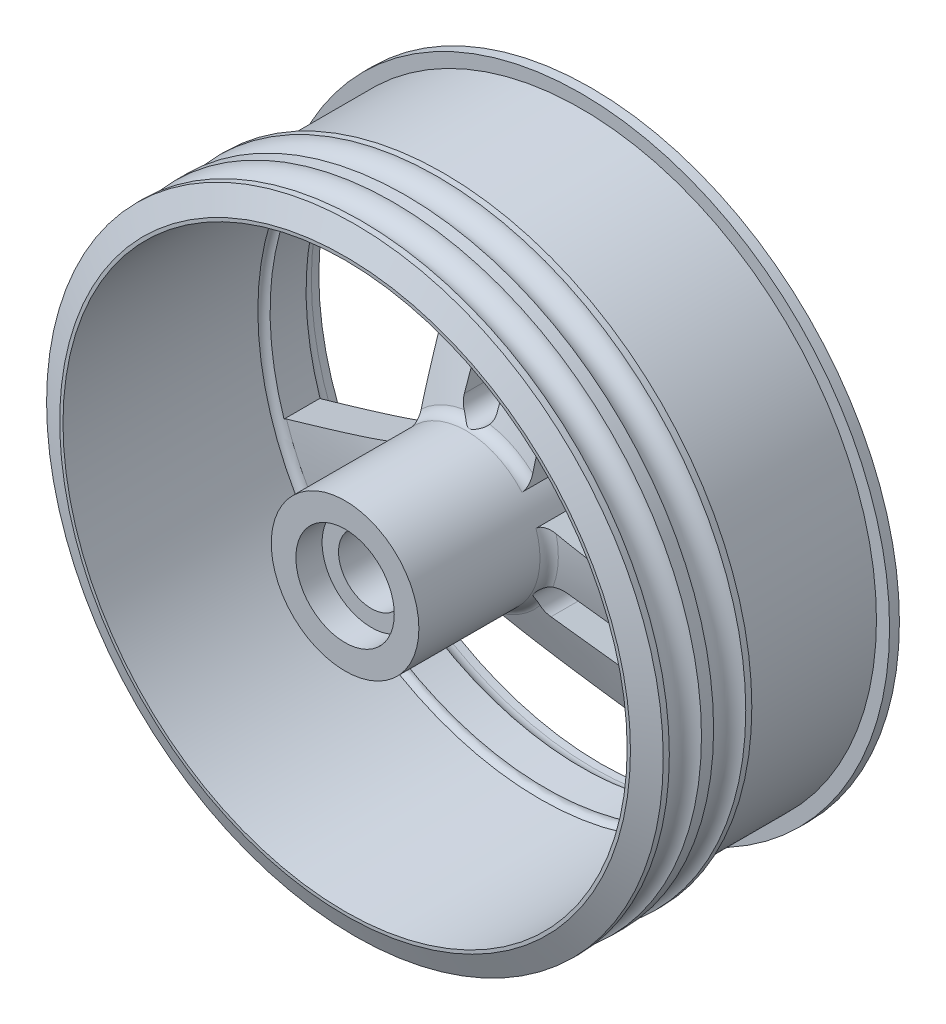
SolidWorks part; units mm, degrees
ref_plane "Front Plane" through (0, 0, 0) normal (0, 0, 1) x (1, 0, 0)
ref_plane "Top Plane" through (0, 0, 0) normal (0, 1, 0) x (1, 0, 0)
ref_plane "Right Plane" through (0, 0, 0) normal (1, 0, 0) x (0, 0, -1)
sketch "Sketch1" plane through (0, 0, 0) normal (0, 1, 0) x (1, 0, 0)
  line L0 (-80.6782, 0) -> (48.2672, 0) construction
  line L1 (0, -31.3399) -> (0, 38.3825) construction
  line L2 (-11.1746, 0) -> (-5, 0)
  line L3 (-43.5, 14) -> (-43, 14)
  line L4 (-47, 11) -> (-47, 12.5)
  line L5 (-43.5, -25) -> (-43, -25)
  line L6 (-11.25, -6.5367) -> (-11.25, -25)
  line L7 (-11.25, -25) -> (-5, -25)
  line L8 (-47, -9.9983) -> (-47, -10.9233)
  line L9 (-41.5876, 10.8525) -> (-11.321, 0.0254)
  line L10 (-47, 11) -> (-45, 11)
  line L11 (-47, -9.9983) -> (-45, -9.9983)
  line L12 (-43, -25) -> (-43, 4.7059)
  line L13 (-12.4048, -4.8972) -> (-41.5431, 5.5263)
  line L14 (-43, 12.8577) -> (-43, 14)
  line L15 (-5, 0) -> (-5, -25)
  line L16 (-43.5, -25) -> (-47, -23.5)
  line L17 (-43.5, 14) -> (-47, 12.5)
  line L18 (-47.5, -20.1228) -> (-47.5, -13.3728) construction
  line L19 (-45, 11) -> (-45, -9.9983)
  line L20 (-47, -23.5) -> (-47, -22.5722)
  line L21 (-47, -15.8222) -> (-47, -17.6733)
  arc A0 (-43, 12.8577) -> (-41.5876, 10.8525) centre (-40.8703, 12.8577) ccw
  arc A1 (-11.1746, 0) -> (-11.321, 0.0254) centre (-11.1746, 0.4349) cw
  arc A2 (-11.25, -6.5367) -> (-12.4048, -4.8972) centre (-12.9913, -6.5367) ccw
  arc A3 (-41.5431, 5.5263) -> (-43, 4.7059) centre (-41.8746, 4.4111) ccw
  arc A4 (-47, -15.8222) -> (-47, -10.9233) centre (-47.5, -13.3728) ccw
  arc A5 (-47, -22.5722) -> (-47, -17.6733) centre (-47.5, -20.1228) ccw
  point P5 (0, 0)
  point P14 (0, -7.4193)
  dimension "D7" = 6.75
  dimension "D5" = 5
  dimension "D6" = 5
  dimension "D1" = 20.9983
  dimension "D2" = 39
  dimension "D3" = 2
  dimension "D4" = 43
  dimension "D8" = 0.5
  dimension "D9" = 47
  dimension "D10" = 1.5
  dimension "D11" = 1.5
  dimension "D12" = 1.5
  dimension "D13" = 0.5
  dimension "D14" = 47.5
  dimension "D15" = 0.925
  dimension "D16" = 5
  dimension "D17" = 5
  dimension "D18" = 11.25
  dimension "D19" = 27.3728
revolve "Revolve2" add sketch "Sketch1" angle 360 about L1
sketch "Sketch2" plane through (0, 0, 0) normal (0, 0, 1) x (1, 0, 0)
  line L0 (0, 0) -> (0, 42) construction
  line L1 (-8.5, 7.3697) -> (-8.5, 41.1309)
  line L2 (8.5, 41.1309) -> (8.5, 7.3697)
  line L3 (2.5, 33.807) -> (2.5, 13.807)
  line L4 (-2.5, 33.807) -> (-2.5, 13.807)
  line L5 (31.3704, -27.9267) -> (2.1323, -11.0461)
  line L6 (28.0277, -19.0686) -> (10.7072, -9.0686)
  line L7 (30.5277, -14.7384) -> (13.2072, -4.7384)
  line L8 (39.8704, -13.2042) -> (10.6323, 3.6764)
  line L9 (-39.8704, -13.2042) -> (-10.6323, 3.6764)
  line L10 (-30.5277, -14.7384) -> (-13.2072, -4.7384)
  line L11 (-28.0277, -19.0686) -> (-10.7072, -9.0686)
  line L12 (-31.3704, -27.9267) -> (-2.1323, -11.0461)
  arc A0 (-31.3704, -27.9267) -> (31.3704, -27.9267) centre (0, 0) ccw
  arc A1 (-8.5, 7.3697) -> (-10.6323, 3.6764) centre (0, 0) ccw
  circle A2 centre (0, 0) radius 11.25 construction
  arc A3 (39.8704, -13.2042) -> (8.5, 41.1309) centre (0, 0) ccw
  arc A4 (-2.5, 13.807) -> (2.5, 13.807) centre (0, 13.807) ccw
  arc A5 (2.5, 33.807) -> (-2.5, 33.807) centre (0, 33.807) ccw
  arc A6 (28.0277, -19.0686) -> (30.5277, -14.7384) centre (29.2777, -16.9035) ccw
  arc A7 (13.2072, -4.7384) -> (10.7072, -9.0686) centre (11.9572, -6.9035) ccw
  arc A8 (-30.5277, -14.7384) -> (-28.0277, -19.0686) centre (-29.2777, -16.9035) ccw
  arc A9 (-10.7072, -9.0686) -> (-13.2072, -4.7384) centre (-11.9572, -6.9035) ccw
  arc A10 (10.6323, 3.6764) -> (8.5, 7.3697) centre (0, 0) ccw
  arc A11 (-2.1323, -11.0461) -> (2.1323, -11.0461) centre (0, 0) ccw
  arc A12 (-8.5, 41.1309) -> (-39.8704, -13.2042) centre (0, 0) ccw
  point P9 (8.5, 24.2503)
  point P42 (0, 0)
  dimension "D3" = 20
  dimension "D2" = 8.5
  dimension "D4" = 3
extrude "Cut-Extrude2" cut sketch "Sketch2" against normal through all both and the other way through all
sketch "Sketch3" plane through (0, 0, 0) normal (0, 0, -1) x (-1, 0, 0)
  circle A0 centre (0, 0) radius 7.5
  dimension "D1" = 15
extrude "Cut-Extrude3" cut sketch "Sketch3" against normal blind 4
sketch "Sketch4" plane through (0, 0, 25) normal (0, 0, 1) x (1, 0, 0)
  circle A0 centre (0, 0) radius 7.5
  dimension "D1" = 15
extrude "Cut-Extrude4" cut sketch "Sketch4" against normal blind 4
